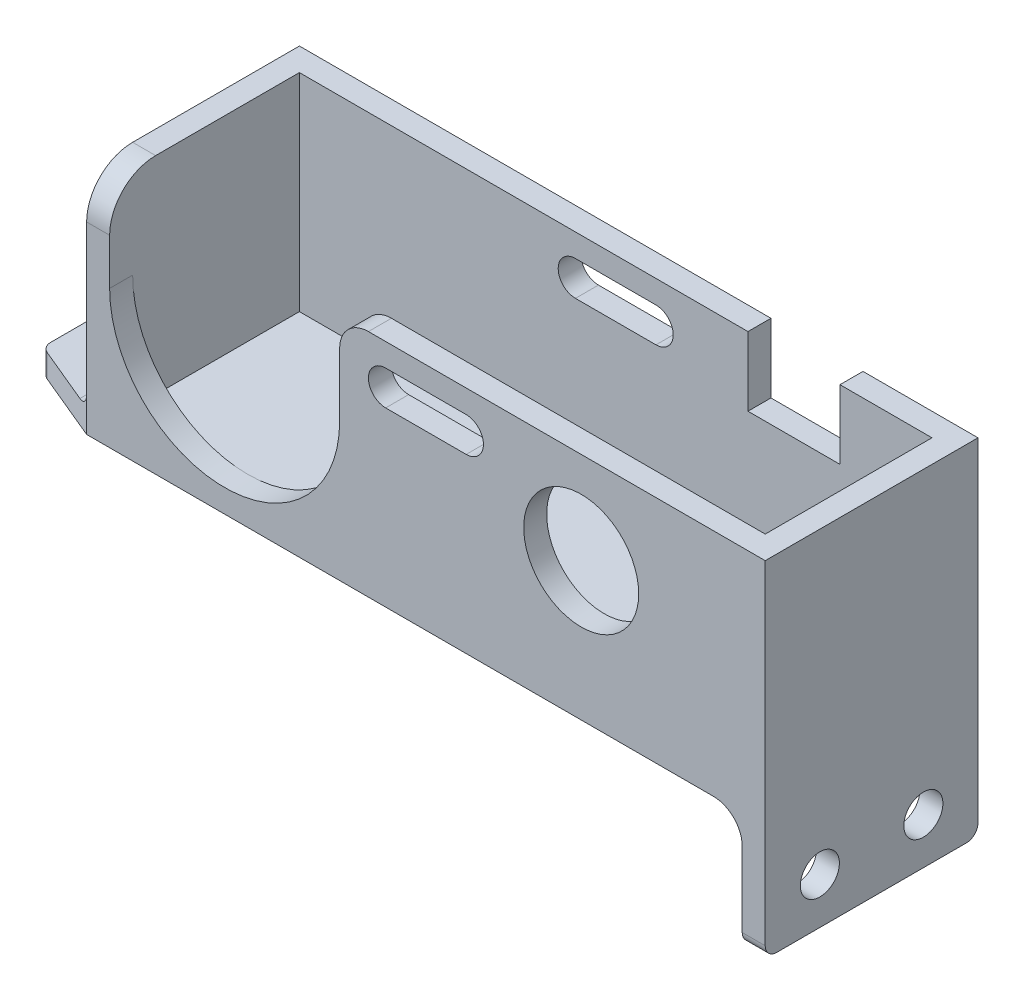
SolidWorks part; units mm, degrees
other "Markup1"
sketch "Sketch4" plane through (-28, -10, 6.5) normal (-0.9519, -0.1137, 0.2847) x (0.2678, 0.1434, 0.9527)
other "Markup2"
sketch "Sketch22" plane through (-36, 9, 9.25) normal (-0.1774, 0.9311, 0.3187) x (-0.0874, 0.3076, -0.9475)
ref_plane "Front Plane" through (0, 0, 0) normal (0, 0, 1) x (1, 0, 0)
ref_plane "Top Plane" through (0, 0, 0) normal (0, 1, 0) x (1, 0, 0)
ref_plane "Right Plane" through (0, 0, 0) normal (1, 0, 0) x (0, 0, -1)
sketch "Sketch1" plane through (0, 0, 0) normal (0, 0, 1) x (1, 0, 0)
  line L0 (-27.5, 0) -> (27.5, 0) construction
  line L1 (-27.5, 9) -> (27.5, 9)
  line L2 (-27.5, -9) -> (27.5, -9)
  line L5 (-27.5, 9) -> (-27.5, -9)
  line L6 (0, 9) -> (0, -9) construction
  line L8 (27.5, 9) -> (27.5, -9)
  point P2 (0, 0)
  dimension "D1" = 55
  dimension "D2" = 18
extrude "Boss-Extrude1" add sketch "Sketch1" along normal mid plane 14.5
shell "Shell2" thickness 2
sketch "Sketch11" plane through (0, 0, 9.25) normal (0, 0, 1) x (1, 0, 0)
  line L0 (-27.5, 9) -> (-27.5, 1)
  line L1 (29.5, 9) -> (-29.5, 9) construction
  line L2 (-7.5, 1) -> (-7.5, 9)
  line L3 (-27.5, 9) -> (-7.5, 9)
  line L4 (-27.5, -9) -> (27.5, -9) construction
  arc A0 (-27.5, 1) -> (-7.5, 1) centre (-17.5, 1) ccw
  dimension "D1" = 10
extrude "lens cutout" cut sketch "Sketch11" against normal up to next
sketch "Sketch12" plane through (0, 0, 9.25) normal (0, 0, 1) x (1, 0, 0)
  line L2 (13.5, 1) -> (-17.5, 1) construction
  circle A0 centre (13.5, 1) radius 5
  arc A1 (-27.5, 1) -> (-7.5, 1) centre (-17.5, 1) ccw construction
  dimension "D2" = 10
  dimension "D1" = 31
extrude "power button hole" cut sketch "Sketch12" against normal up to next
sketch "Sketch13" plane through (0, 0, -9.25) normal (0, 0, -1) x (-1, 0, 0)
  line L2 (-29.5, 9) -> (29.5, 9) construction
  line L3 (-19.5, 9) -> (-11.5, 9)
  line L4 (-19.5, 9) -> (-19.5, 3)
  line L5 (-19.5, 3) -> (-11.5, 3)
  line L6 (-11.5, 9) -> (-11.5, 3)
  arc A0 (7.5, 1) -> (17.5, -9) centre (17.5, 1) ccw construction
  point P0 (17.5, 1)
  dimension "D1" = 29
  dimension "D2" = 2
  dimension "D3" = 8
extrude "power cord cutout" cut sketch "Sketch13" against normal up to next
sketch "Sketch21" plane through (0, 0, 9.25) normal (0, 0, 1) x (1, 0, 0)
  line L0 (-3.5, 5.5) -> (3.5, 5.5) construction
  line L1 (-3.5, 7) -> (3.5, 7)
  line L2 (-3.5, 4) -> (3.5, 4)
  line L3 (29.5, 9) -> (-7.5, 9) construction
  arc A0 (-3.5, 7) -> (-3.5, 4) centre (-3.5, 5.5) ccw
  arc A1 (3.5, 4) -> (3.5, 7) centre (3.5, 5.5) ccw
  point P2 (0, 5.5)
  point P7 (-5, 5.5)
  dimension "D1" = 3
  dimension "D2" = 10
  dimension "D3" = 2
extrude "Cut-Extrude4" cut sketch "Sketch21" against normal through all
fillet "Fillet4" radius 2.5 1 edges at (-7.5, 9, 8.25)
sketch "Sketch15" plane through (0, -11, 0) normal (0, -1, 0) x (1, 0, 0)
  line L0 (-29.5, 9.25) -> (-29.5, -9.25)
  line L1 (-29.5, -9.25) -> (-36, -11.9646)
  line L2 (-36, -11.9646) -> (-36, 6.5354)
  line L3 (-36, 6.5354) -> (-29.5, 9.25)
  dimension "D1" = 67.333
  dimension "D2" = 6.5
extrude "Boss-Extrude3" add sketch "Sketch15" against normal blind 2
hole_wizard "M3 Clearance Hole1" positions "Sketch16" profile "Sketch17" hole size "M3" standard "ANSI Metric" end condition through all
sketch "Sketch16" plane through (0, -9, 0) normal (0, 1, 0) x (1, 0, 0)
  line L0 (-32.75, 10.6073) -> (-32.75, -7.8927) construction
  line L1 (-36, 11.9646) -> (-29.5, 9.25) construction
  line L2 (-29.5, -9.25) -> (-36, -6.5354) construction
  line L6 (-32.75, 1.3573) -> (-36, 1.3573) construction
  line L7 (-36, -6.5354) -> (-36, 11.9646) construction
  point P23 (-32.75, 1.3573)
sketch "Sketch17" plane through (-32.75, -9, -1.3573) normal (1, 0, 0) x (0, 0, 1)
  line L0 (0, 0) -> (0, 2)
  line L1 (0, 2) -> (1.7, 2)
  line L2 (1.7, 2) -> (1.7, 0)
  line L5 (1.7, 0) -> (0, 0)
  line L11 (0, -6.35) -> (0, 107.95) construction
  dimension "Thru Hole Dia." = 3.4
  dimension "Thru Hole Depth" = 2
fillet "Fillet2" radius 1 1 edges at (-29.5, -9, 0)
sketch "Sketch18" plane through (0, -11, 0) normal (0, -1, 0) x (1, 0, 0)
  line L0 (-29.5, -9.25) -> (29.5, -9.25) construction
  line L1 (29.5, 9.25) -> (27.5, 9.25)
  line L2 (29.5, 9.25) -> (29.5, -9.25)
  line L3 (29.5, -9.25) -> (27.5, -9.25)
  line L4 (27.5, 9.25) -> (27.5, -9.25)
  dimension "D1" = 2
extrude "Boss-Extrude4" add sketch "Sketch18" along normal blind 10
hole_wizard "M3 Clearance Hole2" positions "Sketch19" profile "Sketch20" hole size "M3" standard "ANSI Metric" end condition through all
sketch "Sketch19" plane through (27.5, 0, 0) normal (-1, 0, 0) x (0, 0, 1)
  line L0 (0, -21) -> (0, -11) construction
  line L1 (9.25, -21) -> (-9.25, -21) construction
  line L2 (9.25, -11) -> (-9.25, -11) construction
  point P0 (-4.5, -17)
  point P2 (4.5, -17)
  dimension "D1" = 9
  dimension "D2" = 4
sketch "Sketch20" plane through (27.5, -17, -4.5) normal (0, 1, 0) x (0, 0, 1)
  line L0 (0, 0) -> (0, 2)
  line L1 (0, 2) -> (1.7, 2)
  line L2 (1.7, 2) -> (1.7, 0)
  line L5 (1.7, 0) -> (0, 0)
  line L11 (0, -6.35) -> (0, 107.95) construction
  dimension "Thru Hole Dia." = 3.4
  dimension "Thru Hole Depth" = 2
fillet "Fillet3" radius 2.5 1 edges at (27.5, -11, 0)
fillet "Fillet5" radius 4 1 edges at (-28.5, 9, 9.25)
fillet "Fillet6" radius 1 4 edges at (28.5, -21, -9.25) (28.5, -21, 9.25) (-36, -10, -11.9646) (-36, -10, 6.5354)
equation "\"wallthickness\"= 2"
equation "\"D1@Shell2\"=\"wallthickness\""
equation "\"D1@Boss-Extrude3\"=\"wallthickness\""
equation "\"D1@Sketch18\"=\"wallthickness\""
